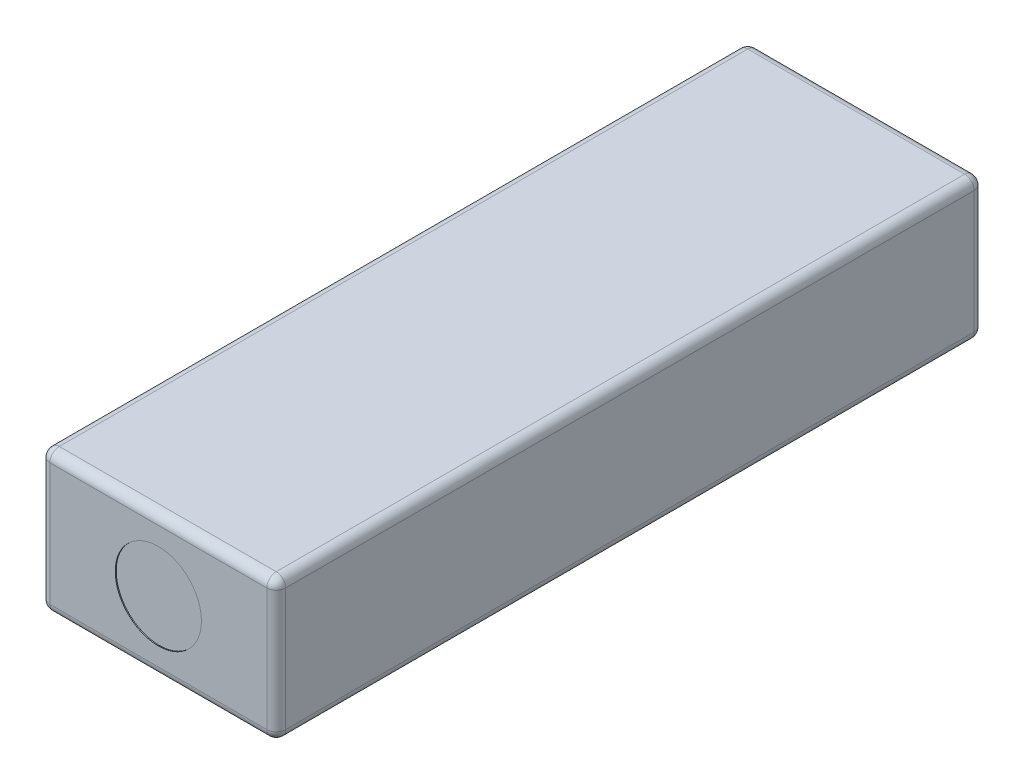
SolidWorks part; units mm, degrees
ref_plane "Front Plane" through (0, 0, 0) normal (0, 0, 1) x (1, 0, 0)
ref_plane "Top Plane" through (0, 0, 0) normal (0, 1, 0) x (1, 0, 0)
ref_plane "Right Plane" through (0, 0, 0) normal (1, 0, 0) x (0, 0, -1)
sketch "Sketch2" plane through (0, 0, 0) normal (0, 1, 0) x (1, 0, 0)
  line L1 (-25, 75) -> (25, 75)
  line L2 (-25, 75) -> (-25, -75)
  line L3 (-25, -75) -> (25, -75)
  line L4 (25, 75) -> (25, -75)
  line L5 (-25, 75) -> (25, -75) construction
  line L6 (-25, -75) -> (25, 75) construction
  point P0 (0, 0)
  dimension "D1" = 50
  dimension "D2" = 150
extrude "Boss-Extrude1" add sketch "Sketch2" along normal blind 30
fillet "Fillet1" radius 2 12 edges at (25, 0, 0) (25, 15, 75) (0, 0, 75) (25, 15, -75) (0, 0, -75) (0, 30, 75) (0, 30, -75) (25, 30, 0) (-25, 15, -75) (-25, 30, 0) (-25, 15, 75) (-25, 0, 0)
sketch "Sketch3" plane through (0, 0, 75) normal (0, 0, 1) x (1, 0, 0)
  circle A0 centre (0, 15) radius 9.1401
extrude "Cut-Extrude1" cut sketch "Sketch3" against normal blind 0.2
